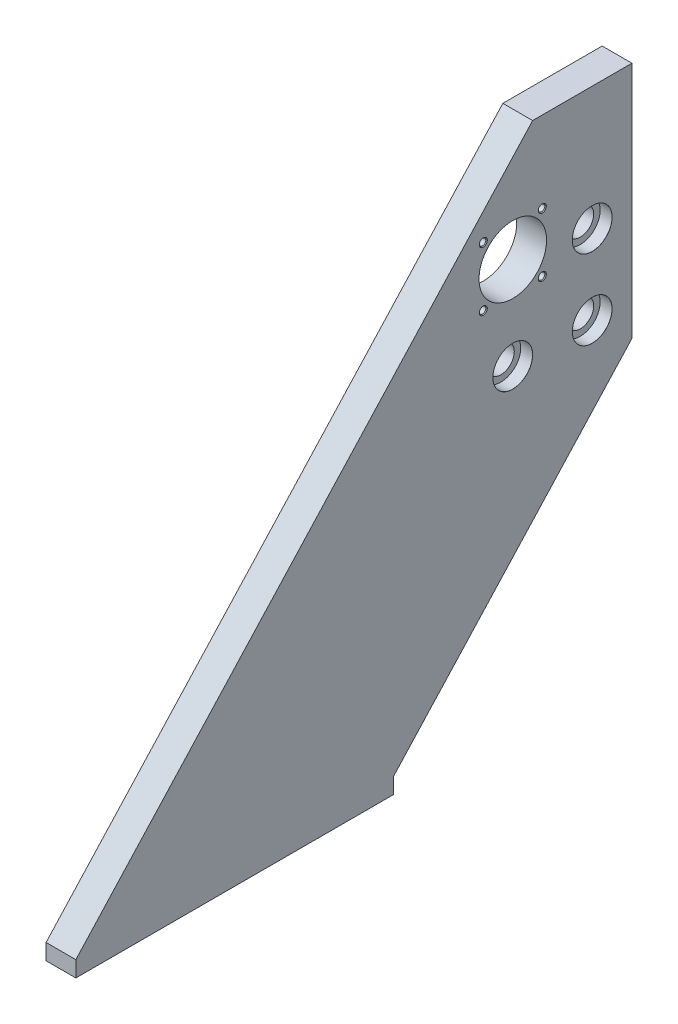
SolidWorks part; units mm, degrees
material "3.1355 (EN-AW 2024)"
ref_plane "Спереди" through (0, 0, 0) normal (0, 0, 1) x (1, 0, 0)
ref_plane "Сверху" through (0, 0, 0) normal (0, 1, 0) x (1, 0, 0)
ref_plane "Справа" through (0, 0, 0) normal (1, 0, 0) x (0, 0, -1)
sketch "Эскиз1" plane through (0, 0, 0) normal (1, 0, 0) x (0, 0, -1)
  line L0 (-80, 0) -> (0, 0)
  line L1 (0, 0) -> (80, 0)
  line L2 (80, 0) -> (80, 8)
  line L5 (200, 258.9091) -> (150, 258.9091)
  line L7 (150, 258.9091) -> (-80, 8)
  line L9 (-80, 8) -> (-80, 0)
  line L10 (80, 8) -> (200, 138.9091)
  line L11 (200, 138.9091) -> (200, 258.9091)
  dimension "D1" = 160
  dimension "D2" = 120
  dimension "D3" = 8
  dimension "D4" = 120
  dimension "D6" = 8
  dimension "D8" = 50
extrude "База" add sketch "Эскиз1" along normal mid plane 15
hole_wizard "Крепление к плите M8" positions "Эскиз2" profile "Эскиз3" tap size "M8" standard "DIN"
sketch "Эскиз2" plane through (0, 0, 0) normal (0, -1, 0) x (-1, 0, 0)
  line L6 (0, 50) -> (0, 0) construction
  line L7 (0, 0) -> (0, -50) construction
  point P3 (0, -50)
  point P5 (0, 50)
  dimension "D1" = 100
sketch "Эскиз3" plane through (0, 0, 50) normal (1, 0, 0) x (0, 0, -1)
  line L0 (0, 0) -> (0, 32.0429)
  line L1 (0, 32.0429) -> (3.4, 30)
  line L2 (3.4, 30) -> (3.4, 0)
  line L5 (3.4, 0) -> (0, 0)
  line L10 (0, 32.0429) -> (-3.4, 30) construction
  line L11 (0, -6.35) -> (0, 107.95) construction
  dimension "Диаметр сверла" = 6.8
  dimension "Глубина сверла" = 30
  dimension "Угол заточки сверла" = 118
cosmetic thread "Отверстие резьбы1" parameters "D1"=25, "D2"=8
cosmetic thread "Отверстие резьбы2" parameters "D1"=25, "D2"=8
hole_wizard "К профилю M12" positions "Эскиз8" profile "Эскиз9" counterbore size "M12" standard "DIN" end condition through all
sketch "Эскиз8" plane through (7.5, 0, 0) normal (1, 0, 0) x (0, 0, -1)
  line L2 (200, 138.9091) -> (200, 258.9091) construction
  line L3 (200, 258.9091) -> (150, 258.9091) construction
  point P0 (180, 196.8091)
  point P2 (180, 156.8091)
  point P11 (140, 156.8091)
  dimension "D1" = 40
  dimension "D2" = 62.1
  dimension "D3" = 20
  dimension "D4" = 40
sketch "Эскиз9" plane through (7.5, 196.8091, -180) normal (0, 1, 0) x (0, 0, -1)
  line L0 (0, 0) -> (0, 15)
  line L1 (0, 15) -> (6.75, 15)
  line L3 (6.75, 15) -> (6.75, 6)
  line L4 (10, 6) -> (6.75, 6)
  line L5 (10, 6) -> (10, 0.025)
  line L6 (10, 0.025) -> (10.025, 0)
  line L7 (10.025, 0) -> (0, 0)
  line L8 (-10, 0.025) -> (-10.025, 0) construction
  line L11 (0, -6.35) -> (0, 107.95) construction
  dimension "Диаметр сквозного отверстия" = 13.5
  dimension "Глубина сквозного отверстия" = 15
  dimension "Диаметр цековки" = 20
  dimension "Глубина цековки" = 6
  dimension "Диаметр передней зенковки" = 20.05
  dimension "Угол передней зенковки" = 90
sketch "Эскиз10" plane through (7.5, 0, 0) normal (1, 0, 0) x (0, 0, -1)
  line L0 (200, 138.9091) -> (200, 258.9091) construction
  line L1 (-80, 0) -> (80, 0) construction
  circle A0 centre (140, 203.3) radius 17
  dimension "D1" = 34
  dimension "D2" = 60
  dimension "D3" = 203.3
extrude "Вырез-Вытянуть1" cut sketch "Эскиз10" against normal through all
sketch "Эскиз11" plane through (7.5, 0, 0) normal (1, 0, 0) x (0, 0, -1)
  line L1 (125.1508, 188.4508) -> (154.8492, 188.4508)
  line L2 (125.1508, 188.4508) -> (125.1508, 218.1492)
  line L3 (125.1508, 218.1492) -> (154.8492, 218.1492)
  line L4 (154.8492, 188.4508) -> (154.8492, 218.1492)
  line L5 (125.1508, 188.4508) -> (154.8492, 218.1492) construction
  line L6 (125.1508, 218.1492) -> (154.8492, 188.4508) construction
  circle A1 centre (154.8492, 218.1492) radius 1.5
  circle A2 centre (154.8492, 188.4508) radius 1.5
  circle A3 centre (125.1508, 188.4508) radius 1.5
  circle A4 centre (125.1508, 218.1492) radius 1.5
  point P0 (140, 203.3)
  point P1 (140, 203.3)
  dimension "D1" = 42
  dimension "D2" = 3
hole_wizard "FK10 - M4" positions "Эскиз12" profile "Эскиз13" tap size "M4" standard "DIN" end condition through all
sketch "Эскиз12" plane through (7.5, 0, 0) normal (1, 0, 0) x (0, 0, -1)
  point P0 (154.8492, 218.1492)
  point P3 (154.8492, 188.4508)
  point P6 (125.1508, 188.4508)
  point P9 (125.1508, 218.1492)
sketch "Эскиз13" plane through (7.5, 218.1492, -154.8492) normal (0, 1, 0) x (0, 0, -1)
  line L0 (0, 0) -> (0, 15)
  line L1 (0, 15) -> (1.65, 15)
  line L2 (1.65, 15) -> (1.65, 0.375)
  line L3 (1.65, 0.375) -> (2.025, 0)
  line L5 (2.025, 0) -> (0, 0)
  line L6 (-1.65, 0.375) -> (-2.025, 0) construction
  line L11 (0, -6.35) -> (0, 107.95) construction
  dimension "Диаметр проходного сверла" = 3.3
  dimension "Глубина проходного сверла" = 15
  dimension "Диаметр передней зенковки" = 4.05
  dimension "Угол передней зенковки" = 90
cosmetic thread "Отверстие резьбы3" parameters "D2"=4
cosmetic thread "Отверстие резьбы4" parameters "D2"=4
cosmetic thread "Отверстие резьбы5" parameters "D2"=4
cosmetic thread "Отверстие резьбы6" parameters "D2"=4
